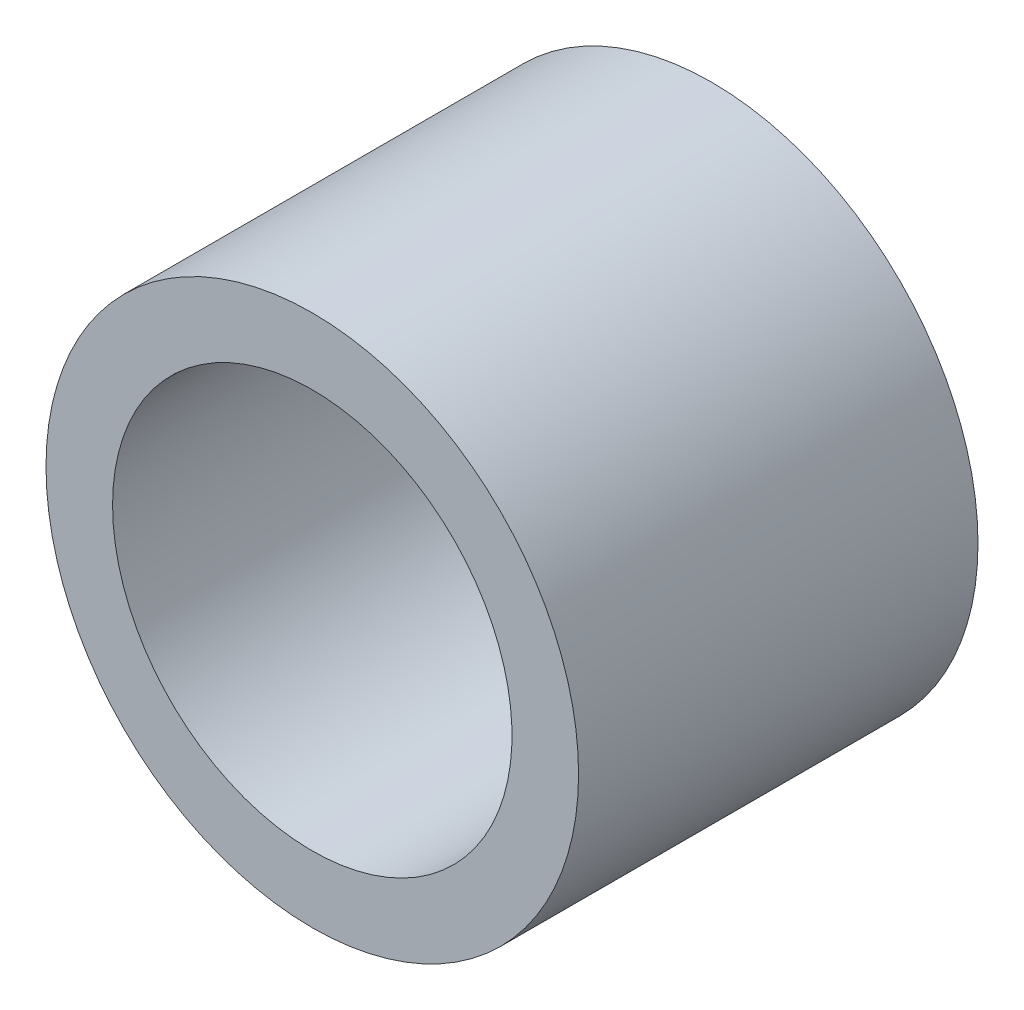
SolidWorks part; units mm, degrees
material "Tin Bearing Bronze"
ref_plane "Front Plane" through (0, 0, 0) normal (0, 0, 1) x (1, 0, 0)
ref_plane "Top Plane" through (0, 0, 0) normal (0, 1, 0) x (1, 0, 0)
ref_plane "Right Plane" through (0, 0, 0) normal (1, 0, 0) x (0, 0, -1)
sketch "Sketch1" plane through (0, 0, 0) normal (0, 0, 1) x (1, 0, 0)
  circle A0 centre (0, 0) radius 4.7625
  circle A1 centre (0, 0) radius 6.35
  dimension "D1" = 9.525
  dimension "D2" = 12.7
extrude "Boss-Extrude1" add sketch "Sketch1" along normal blind 9.525
equation "\"dovetail-angle\" = 55"
equation "\"dovetail-stock-width\" = 5"
equation "\"dovetail-stock-height\" = 1.25"
equation "\"dovetail-depth\" = 0.5 * \"dovetail-stock-height\""
equation "\"dovetail-throat-width\" = \"dovetail-stock-width\" - (2 * \"dovetail-depth\")"
equation "\"delta-x\" = 6"
equation "\"delta-y\" = 3"
equation "\"delta-z\"= 2.5"
equation "\"gib-thickness\" = 0.25"
equation "\"x-slide-length\" = \"dovetail-stock-width\" + \"delta-x\""
equation "\"y-slide-length\" = \"dovetail-stock-width\" + \"delta-y\""
equation "\"dog-point-diam\" = .149"
equation "\"dog-point-length\" = .067"
equation "\"dovetail-double-height\" = 2 * \"dovetail-depth\" + 0.5"
equation "\"acme-major-diam\" = .5"
equation "\"acme-pitch-diam\" = 0.45"
equation "\"acme-minor-diam\" = 0.4"
equation "\"x-screw-length\" = \"x-slide-length\" + \"screw-add-length\""
equation "\"y-screw-length\" = \"y-slide-length\" + \"screw-add-length\""
equation "\"acme-nut-od\" = 1.47"
equation "\"acme-nut-length\" = 1"
equation "\"acme-nut-trim-height\" = .75"
equation "\"screw-bearing-od\" = 0.5"
equation "\"screw-bearing-length\" = .375"
equation "\"end-plate-thickness\" = \"screw-bearing-length\""
equation "\"screw-bearing-id\" = .375"
equation "\"D1@Sketch1\"=\"screw-bearing-id\""
equation "\"D2@Sketch1\"=\"screw-bearing-od\""
equation "\"D1@Boss-Extrude1\"=\"screw-bearing-length\""
